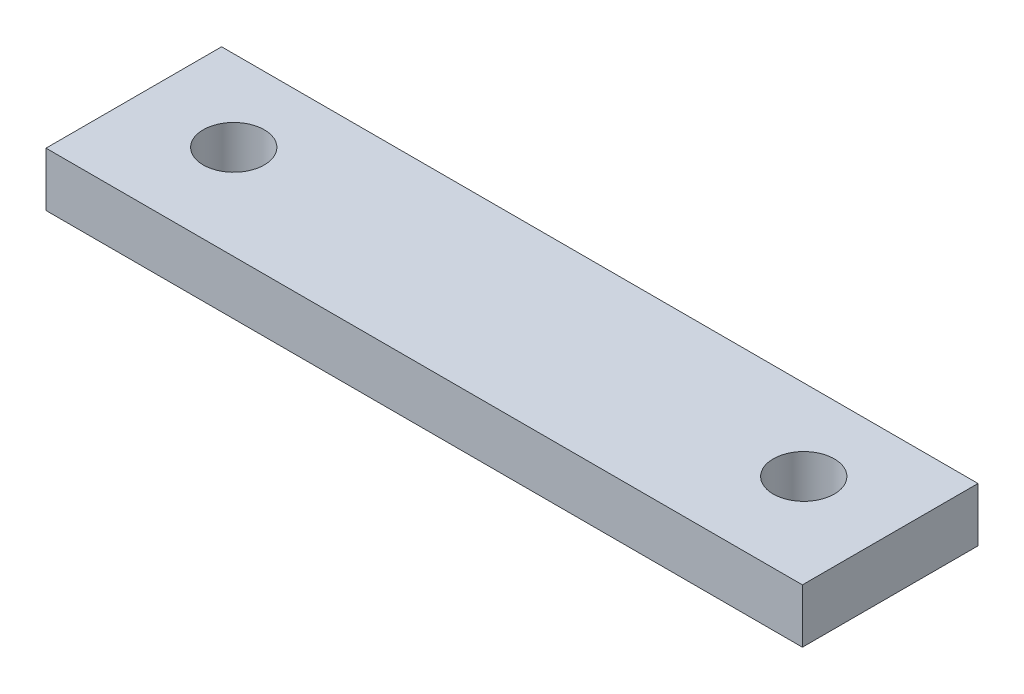
SolidWorks part; units mm, degrees
ref_plane "Front Plane" through (0, 0, 0) normal (0, 0, 1) x (1, 0, 0)
ref_plane "Top Plane" through (0, 0, 0) normal (0, 1, 0) x (1, 0, 0)
ref_plane "Right Plane" through (0, 0, 0) normal (1, 0, 0) x (0, 0, -1)
sketch "Sketch1" plane through (0, 0, 0) normal (0, 1, 0) x (1, 0, 0)
  line L0 (-13.3985, 0) -> (13.3985, 0) construction
  line L1 (-17.78, 3.81) -> (-17.78, -4.445)
  line L2 (-17.78, -4.445) -> (17.78, -4.445)
  line L3 (17.78, -4.445) -> (17.78, 3.81)
  line L4 (17.78, 3.81) -> (-17.78, 3.81)
  line L5 (13.3985, 0) -> (17.78, 0) construction
  line L6 (-13.3985, 0) -> (-17.78, 0) construction
  circle A2 centre (-13.3985, 0) radius 1.4351
  circle A3 centre (13.3985, 0) radius 1.4351
  dimension "D2" = 2.8702
  dimension "D1" = 26.797
  dimension "D3" = 3.81
  dimension "D4" = 4.445
  dimension "D5" = 4.3815
extrude "Boss-Extrude1" add sketch "Sketch1" along normal blind 2.54
